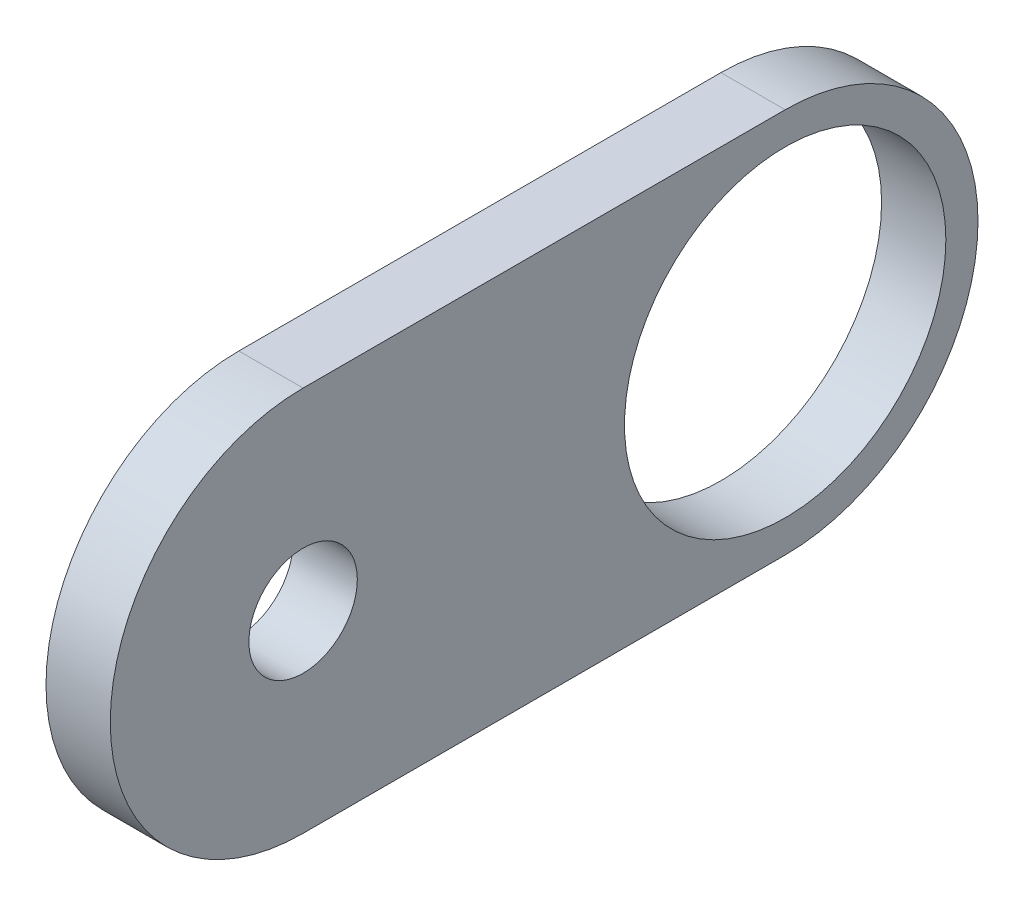
SolidWorks part; units mm, degrees
material "Ti-6Al-4VSolution treated and aged (SS)"
ref_plane "Front Plane" through (0, 0, 0) normal (1, 0, 0) x (0, 1, 0)
ref_plane "Top Plane" through (0, 0, 0) normal (0, 0, 1) x (0, 1, 0)
ref_plane "Right Plane" through (0, 0, 0) normal (0, 1, 0) x (-1, 0, 0)
sketch "Sketch1" plane through (0, 0, 0) normal (1, 0, 0) x (0, 1, 0)
  line L0 (-60.8736, 15.3619) -> (-60.8736, -22.7381)
  line L1 (-30.3936, -22.7381) -> (-30.3936, 15.3619)
  arc A0 (-60.8736, 15.3619) -> (-30.3936, 15.3619) centre (-45.6336, 15.3619) cw
  arc A1 (-60.8736, -22.7381) -> (-30.3936, -22.7381) centre (-45.6336, -22.7381) ccw
  circle A2 centre (-45.6336, -22.7381) radius 12.7
  circle A3 centre (-45.6336, 15.3619) radius 4.285
  dimension "D1" = 25.4
  dimension "D2" = 8.57
  dimension "D3" = 30.48
  dimension "D4" = 38.1
extrude "Boss-Extrude1" add sketch "Sketch1" along normal blind 5.08
equation "\"d_max\"= 1.000"
equation "\"F\"= 600"
equation "\"YieldStr\"= 120000.0006"
equation "\"SF\"= 4"
equation "\"A_min\"= ( \"F\" * \"SF\" ) / ( \"YieldStr\" )"
equation "\"x\"= 0.10"
equation "\"y\"= \"A_min\" / \"x\""
equation "\"width\"= 2 * ( ( \"d_max\" / 2 ) + \"x\" )"
equation "\"d_top\"= 0.3374"
equation "\"D1@Sketch1\"=\"d_max\""
equation "\"D2@Sketch1\"=\"d_top\""
equation "\"D3@Sketch1\"=\"width\""
equation "\"r_max\"= \"d_max\" / 2"
equation "\"D4@Sketch1\"=\"d_max\"+\"r_max\""
equation "\"D1@Boss-Extrude1\"=\"y\""
